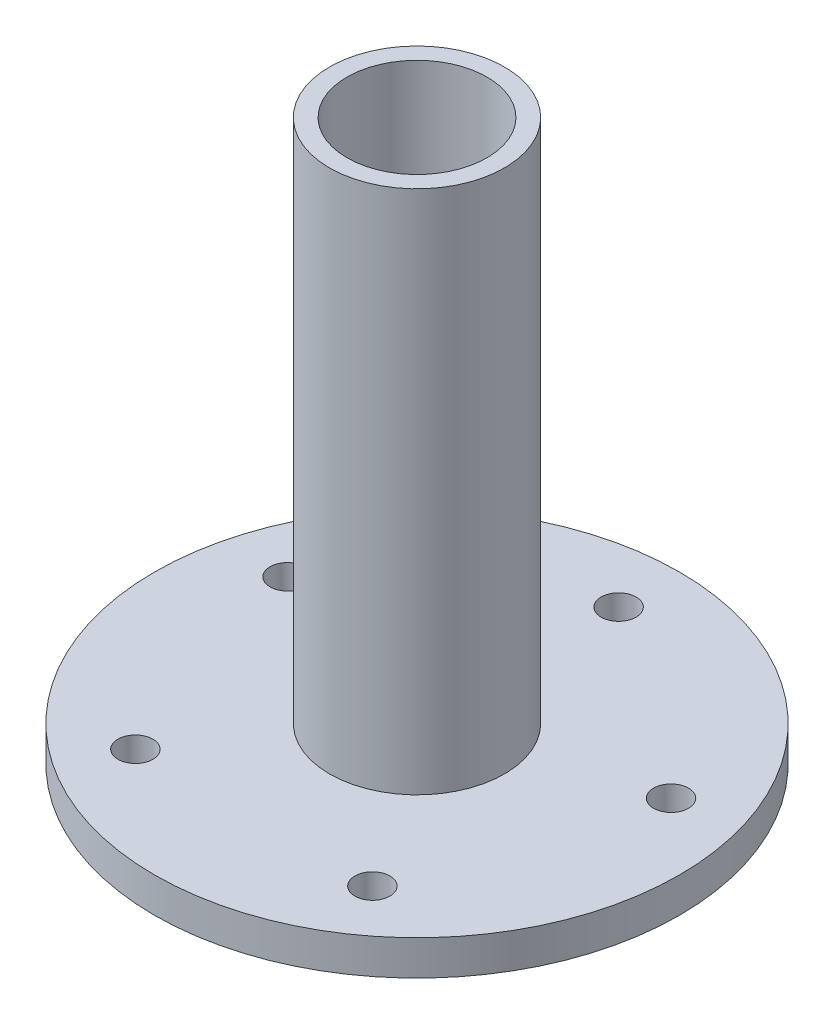
SolidWorks part; units mm, degrees
ref_plane "Front Plane" through (0, 0, 0) normal (0, 0, 1) x (1, 0, 0)
ref_plane "Top Plane" through (0, 0, 0) normal (0, 1, 0) x (1, 0, 0)
ref_plane "Right Plane" through (0, 0, 0) normal (1, 0, 0) x (0, 0, -1)
sketch "Sketch1" plane through (0, 0, 0) normal (0, 1, 0) x (1, 0, 0)
  circle A0 centre (0, 0) radius 75
  dimension "D1" = 150
extrude "Boss-Extrude1" add sketch "Sketch1" along normal blind 10
sketch "Sketch2" plane through (0, 10, 0) normal (0, 1, 0) x (1, 0, 0)
  circle A1 centre (0, 57.6148) radius 5
  circle A2 centre (54.7949, 17.804) radius 5
  circle A3 centre (33.8651, -46.6114) radius 5
  circle A4 centre (-33.8651, -46.6114) radius 5
  circle A5 centre (-54.7949, 17.804) radius 5
  point P13 (0, 0)
  dimension "D1" = 5
  dimension "D2" = 10
extrude "Cut-Extrude1" cut sketch "Sketch2" against normal blind 10
sketch "Sketch3" plane through (0, 10, 0) normal (0, 1, 0) x (1, 0, 0)
  circle A0 centre (0, 0) radius 20
  dimension "D1" = 40
extrude "Cut-Extrude2" cut sketch "Sketch3" against normal blind 10
sketch "Sketch4" plane through (0, 10, 0) normal (0, 1, 0) x (1, 0, 0)
  circle A0 centre (0, 0) radius 20
  circle A1 centre (0, 0) radius 25
  dimension "D1" = 50
  dimension "D2" = 40
extrude "Boss-Extrude2" add sketch "Sketch4" along normal blind 150
